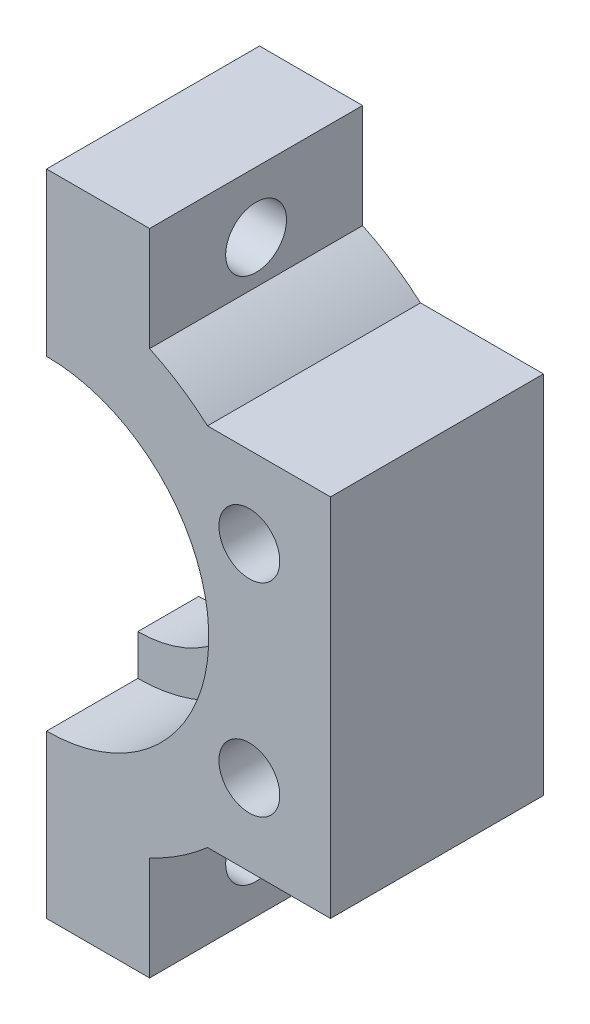
SolidWorks part; units mm, degrees
ref_plane "Front Plane" through (0, 0, 0) normal (0, 0, 1) x (1, 0, 0)
ref_plane "Top Plane" through (0, 0, 0) normal (0, 1, 0) x (1, 0, 0)
ref_plane "Right Plane" through (0, 0, 0) normal (1, 0, 0) x (0, 0, -1)
sketch "Sketch2" plane through (0, 0, 0) normal (0, 0, 1) x (1, 0, 0)
  line L0 (7.9373, 9) -> (14, 9)
  line L1 (14, 9) -> (14, -9)
  line L2 (14, -9) -> (7.9373, -9)
  line L3 (0, 9) -> (0, 6)
  line L4 (0, 9) -> (0, 16)
  line L5 (0, 16) -> (5.0818, 16)
  line L6 (5.0818, 16) -> (5.0818, 10.8708)
  line L7 (5.0818, -10.8708) -> (5.0818, -16)
  line L8 (5.0818, -16) -> (0, -16)
  line L9 (0, -16) -> (0, -9)
  line L10 (0, -6) -> (0, -9)
  arc A0 (0, -6) -> (0, 6) centre (0, 0) ccw
  arc A2 (5.0818, -10.8708) -> (7.9373, -9) centre (0, 0) ccw
  circle A3 centre (10, 5) radius 1.5
  circle A4 centre (10, -5) radius 1.5
  arc A7 (7.9373, 9) -> (5.0818, 10.8708) centre (0, 0) ccw
  dimension "D1" = 12
  dimension "D3" = 24
  dimension "D8" = 3
  dimension "D4" = 4
  dimension "D5" = 4
  dimension "D6" = 4
  dimension "D7" = 4
  dimension "D9" = 16
  dimension "D10" = 32
  dimension "D11" = 14
extrude "Boss-Extrude1" add sketch "Sketch2" along normal blind 10.5
sketch "Sketch3" plane through (0, 0, 10.5) normal (0, 0, 1) x (1, 0, 0)
  circle A0 centre (0, 0) radius 8
  dimension "D1" = 16
extrude "Cut-Extrude1" cut sketch "Sketch3" against normal blind 4.5
sketch "Sketch5" plane through (5.0818, 0, 0) normal (1, 0, 0) x (0, 0, -1)
  line L0 (0, -16) -> (0, -10.8708) construction
  line L1 (0, 10.8708) -> (0, 16) construction
  line L2 (-10.5, 16) -> (0, 16) construction
  line L3 (-10.5, -16) -> (0, -16) construction
  circle A0 centre (-5.25, 13) radius 1.5
  circle A1 centre (-5.25, -13) radius 1.5
  point P6 (0, -13.4354)
  point P9 (0, 13.4354)
  dimension "D1" = 3
  dimension "D2" = 5.25
  dimension "D3" = 5.25
  dimension "D4" = 3
  dimension "D5" = 3
extrude "Cut-Extrude3" cut sketch "Sketch5" against normal through all
sketch "Sketch4" plane through (0, 0, 0) normal (0, 0, -1) x (-1, 0, 0)
  circle A0 centre (0, 0) radius 8
  dimension "D1" = 16
extrude "Cut-Extrude2" cut sketch "Sketch4" against normal blind 3
